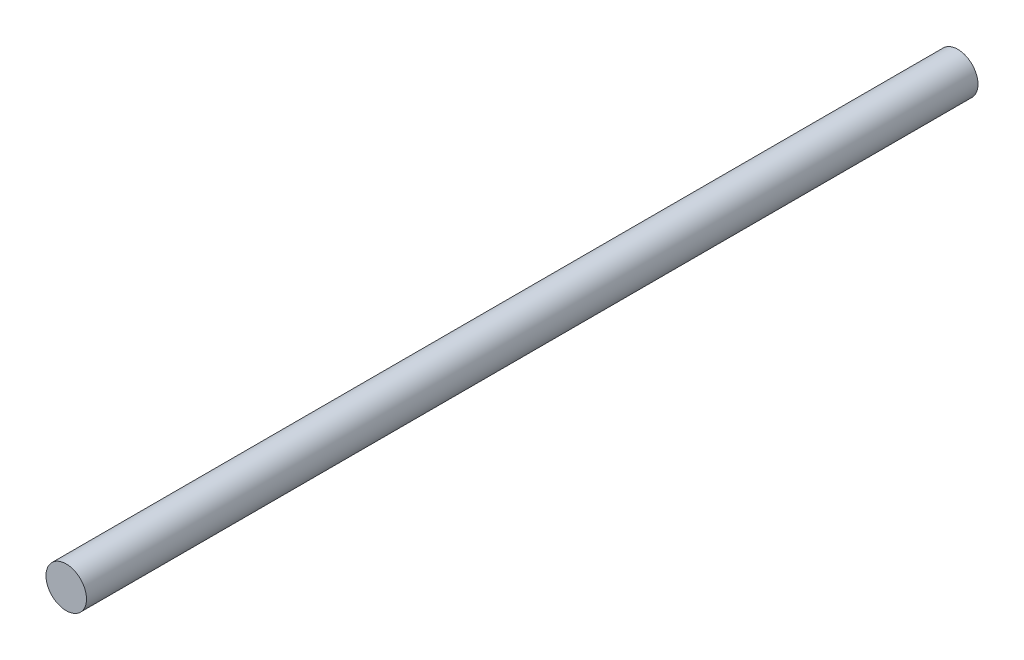
SolidWorks part; units mm, degrees
ref_plane "Front" through (0, 0, 0) normal (0, 0, 1) x (1, 0, 0)
ref_plane "Top" through (0, 0, 0) normal (0, 1, 0) x (1, 0, 0)
ref_plane "Right" through (0, 0, 0) normal (1, 0, 0) x (0, 0, -1)
sketch "Sketch1" plane through (0, 0, 0) normal (0, 0, 1) x (1, 0, 0)
  circle A0 centre (0, 0) radius 2.5
  dimension "D1" = 5
extrude "Boss-Extrude1" add sketch "Sketch1" along normal blind 110
equation "\"D1@Sketch1\"=5mm"
